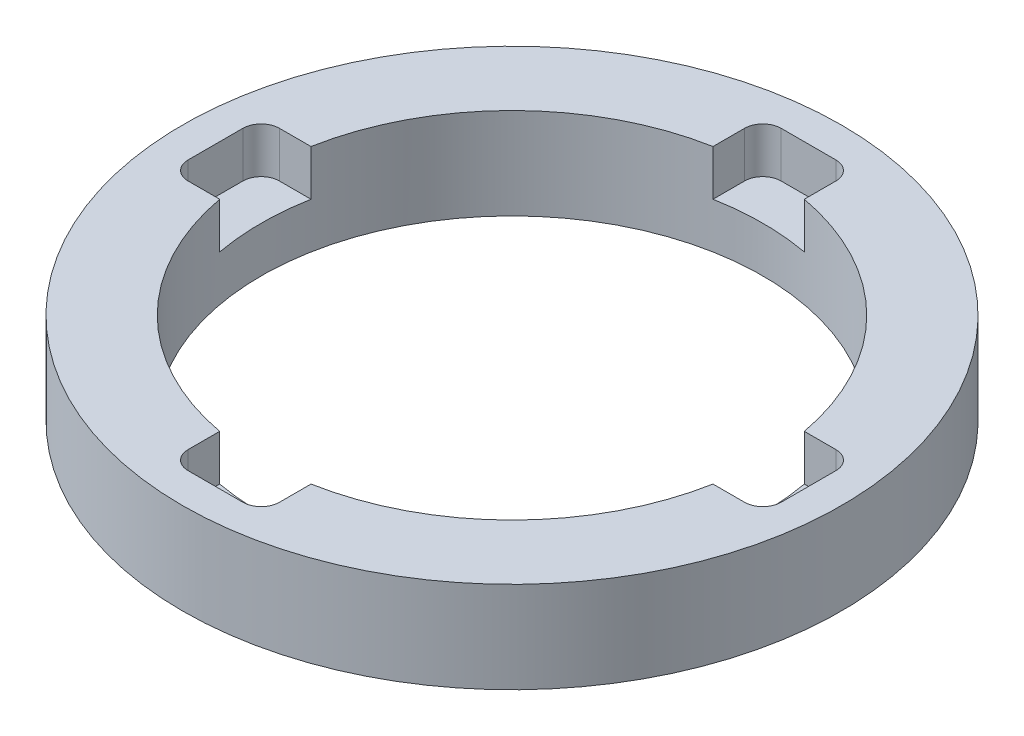
SolidWorks part; units mm, degrees
material "6061 Alloy"
ref_plane "Front Plane" through (0, 0, 0) normal (0, 0, 1) x (1, 0, 0)
ref_plane "Top Plane" through (0, 0, 0) normal (0, 1, 0) x (1, 0, 0)
ref_plane "Right Plane" through (0, 0, 0) normal (1, 0, 0) x (0, 0, -1)
sketch "Sketch1" plane through (0, 0, 0) normal (0, 1, 0) x (1, 0, 0)
  circle A0 centre (0, 0) radius 45.8343
  circle A1 centre (0, 0) radius 34.8869
  dimension "D1" = 91.6686
  dimension "D2" = 10.9474
extrude "Boss-Extrude1" add sketch "Sketch1" along normal blind 12.7
sketch "Sketch2" plane through (0, 12.7, 0) normal (0, 1, 0) x (1, 0, 0)
  line L2 (6.35, 34.3041) -> (6.35, 38.6969)
  line L3 (3.81, 41.2369) -> (-3.81, 41.2369)
  line L4 (-6.35, 34.3041) -> (-6.35, 38.6969)
  line L5 (0, 41.2369) -> (0, 34.8869) construction
  circle A0 centre (0, 0) radius 34.8869 construction
  arc A1 (6.35, 34.3041) -> (-6.35, 34.3041) centre (0, 0) ccw
  arc A2 (6.35, 38.6969) -> (3.81, 41.2369) centre (3.81, 38.6969) ccw
  arc A3 (-3.81, 41.2369) -> (-6.35, 38.6969) centre (-3.81, 38.6969) ccw
  point P0 (0, 0)
  point P10 (6.35, 41.2369)
  point P13 (-6.35, 41.2369)
  dimension "D3" = 2.54
  dimension "D1" = 12.7
  dimension "D2" = 6.35
extrude "Cut-Extrude1" cut sketch "Sketch2" against normal blind 6.35
pattern_circular "CirPattern1" count 4 over 360 about axis through (0, 0, 0) along (0, 1, 0) of "Cut-Extrude1"
